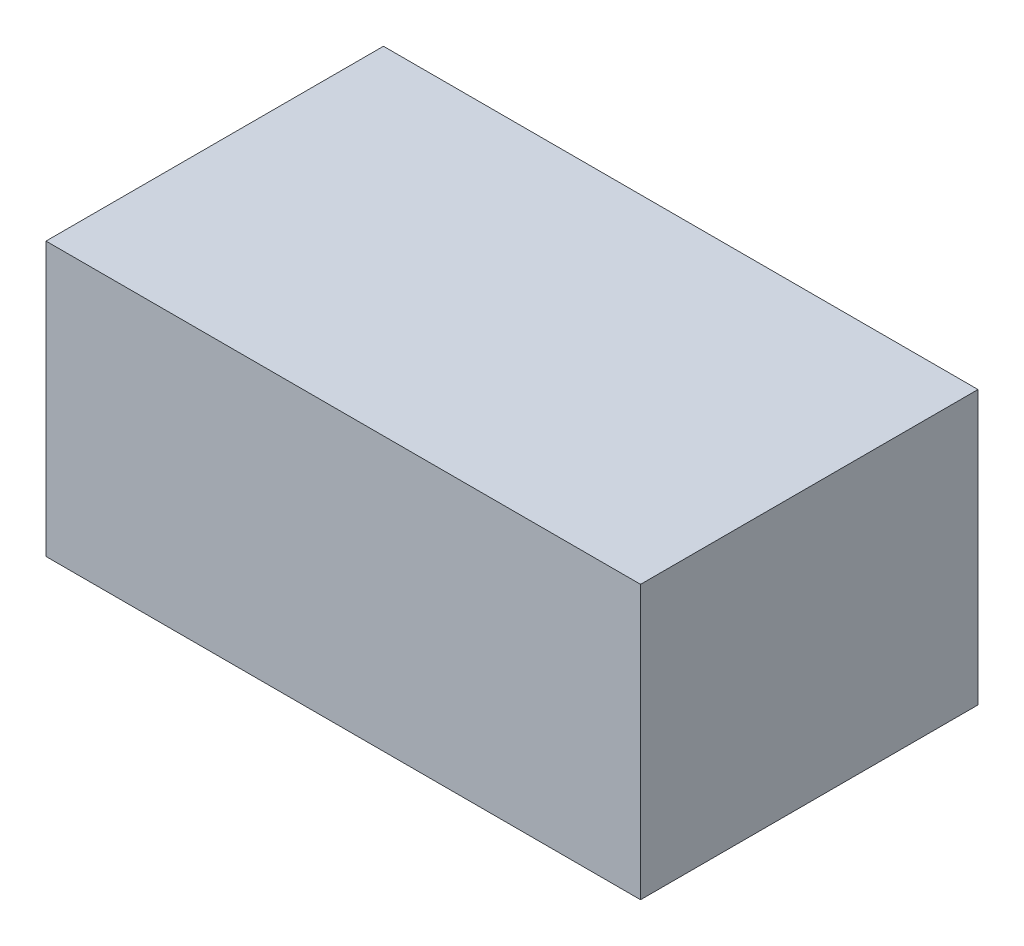
SolidWorks part; units mm, degrees
ref_plane "Front Plane" through (0, 0, 0) normal (0, 0, 1) x (1, 0, 0)
ref_plane "Top Plane" through (0, 0, 0) normal (0, 1, 0) x (1, 0, 0)
ref_plane "Right Plane" through (0, 0, 0) normal (1, 0, 0) x (0, 0, -1)
sketch "Sketch1" plane through (0, 0, 0) normal (0, 1, 0) x (1, 0, 0)
  line L1 (-23.8226, -42.2258) -> (13.1774, -42.2258)
  line L2 (-23.8226, -42.2258) -> (-23.8226, -21.2258)
  line L3 (-23.8226, -21.2258) -> (13.1774, -21.2258)
  line L4 (13.1774, -42.2258) -> (13.1774, -21.2258)
  dimension "D1" = 21
  dimension "D2" = 37
extrude "Boss-Extrude1" add sketch "Sketch1" along normal blind 17
sketch "Sketch4" plane through (0, 0, 21.2258) normal (0, 0, -1) x (-1, 0, 0)
  line L6 (-11.3024, 15) -> (21.9476, 15)
  line L7 (-11.3024, 15) -> (-11.3024, 2)
  line L8 (-11.3024, 2) -> (21.9476, 2)
  line L9 (21.9476, 15) -> (21.9476, 2)
  dimension "D1" = 33.25
  dimension "D2" = 13
extrude "Cut-Extrude1" cut sketch "Sketch4" against normal blind 19 contours L6 L9 L8 L7
